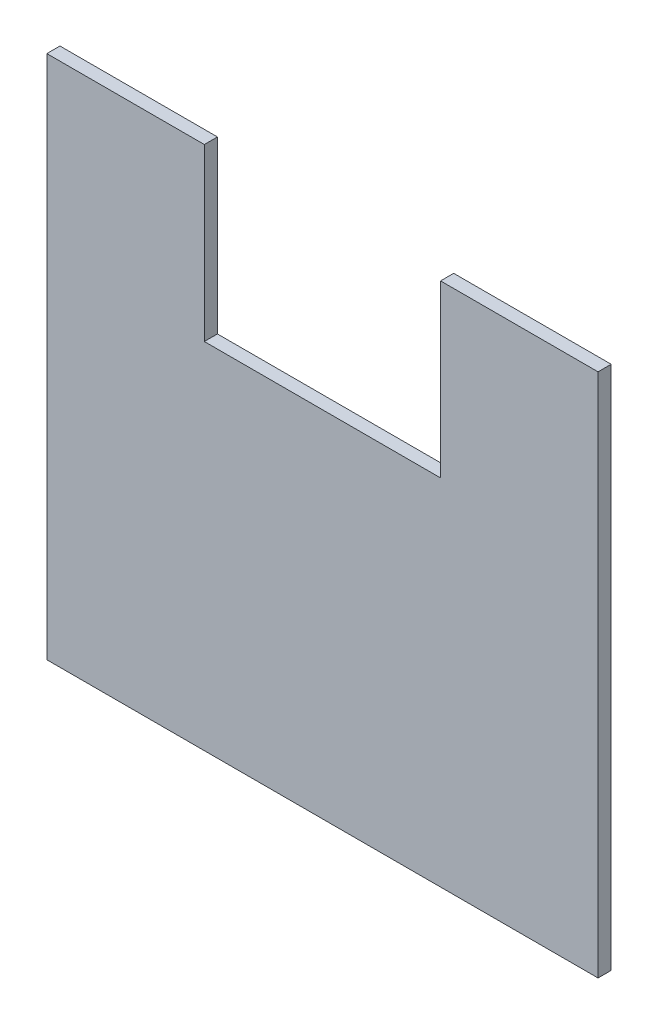
SolidWorks part; units mm, degrees
ref_plane "Front Plane" through (0, 0, 0) normal (0, 0, 1) x (1, 0, 0)
ref_plane "Top Plane" through (0, 0, 0) normal (0, 1, 0) x (1, 0, 0)
ref_plane "Right Plane" through (0, 0, 0) normal (1, 0, 0) x (0, 0, -1)
sketch "Sketch1" plane through (0, 0, 0) normal (0, 0, 1) x (1, 0, 0)
  line L0 (-210, 200) -> (-150, 200)
  line L1 (-150, 200) -> (-150, 135)
  line L2 (-150, 135) -> (-60, 135)
  line L3 (-60, 135) -> (-60, 200)
  line L4 (-60, 200) -> (0, 200)
  line L5 (0, 200) -> (0, 0)
  line L6 (0, 0) -> (-210, 0)
  line L7 (-210, 0) -> (-210, 200)
  point P8 (-25.4837, -26.2609)
  dimension "D1" = 200
  dimension "D2" = 60
  dimension "D3" = 65
  dimension "D4" = 65
  dimension "D5" = 60
  dimension "D6" = 90
extrude "Boss-Extrude1" add sketch "Sketch1" along normal blind 5
